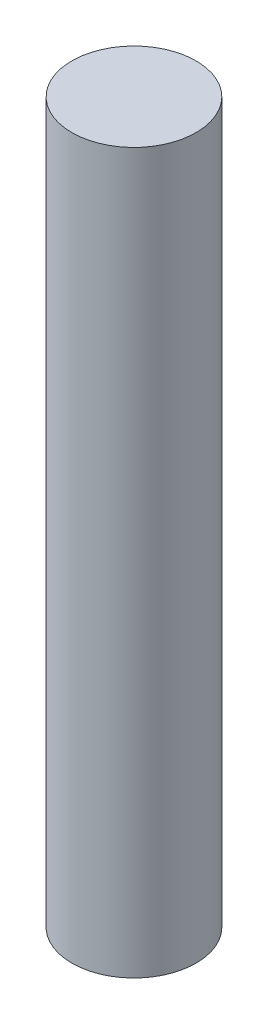
SolidWorks part; units mm, degrees
material "AISI 1020"
ref_plane "Front Plane" through (0, 0, 0) normal (0, 0, 1) x (1, 0, 0)
ref_plane "Top Plane" through (0, 0, 0) normal (0, 1, 0) x (1, 0, 0)
ref_plane "Right Plane" through (0, 0, 0) normal (1, 0, 0) x (0, 0, -1)
sketch "Sketch1" plane through (0, 0, 0) normal (0, 1, 0) x (1, 0, 0)
  circle A0 centre (0, 0) radius 42.5
  dimension "D1" = 85
extrude "Boss-Extrude1" add sketch "Sketch1" along normal blind 492
equation "\"link2Diameter\"=85"
equation "\"D1@Sketch1\"=\"link2Diameter\""
